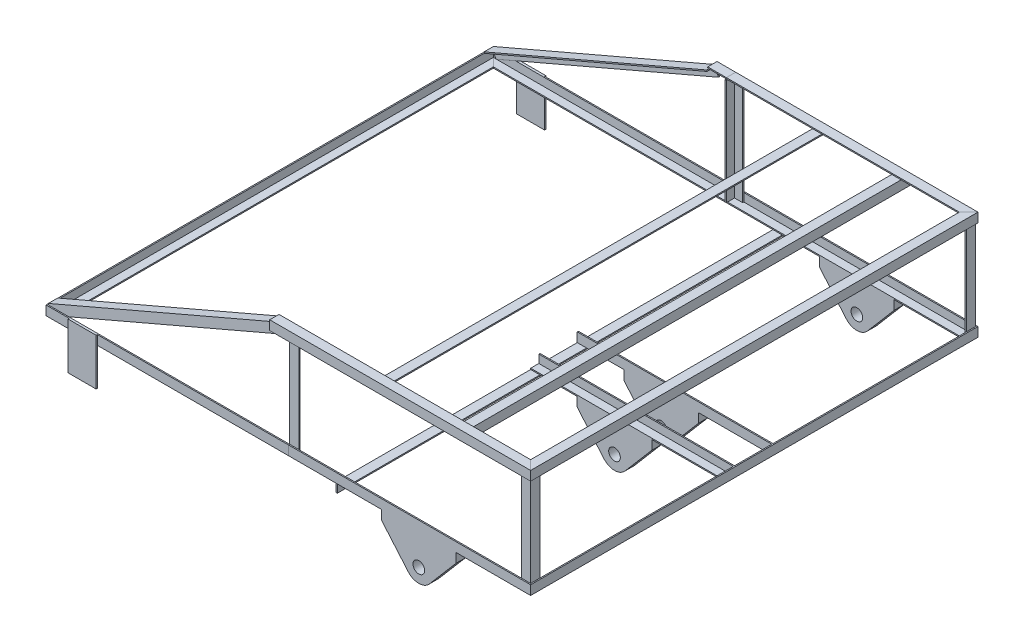
SolidWorks part; units mm, degrees
ref_plane "Front Plane" through (0, 0, 0) normal (0, 0, 1) x (1, 0, 0)
ref_plane "Top Plane" through (0, 0, 0) normal (0, 1, 0) x (1, 0, 0)
ref_plane "Right Plane" through (0, 0, 0) normal (1, 0, 0) x (0, 0, -1)
sketch "Sketch1" plane through (0, 0, 0) normal (0, 1, 0) x (1, 0, 0)
  line L1 (-330.2, -304.8) -> (330.2, -304.8)
  line L2 (-330.2, -304.8) -> (-330.2, 304.8)
  line L3 (-330.2, 304.8) -> (330.2, 304.8)
  line L4 (330.2, -304.8) -> (330.2, 304.8)
  line L5 (-330.2, -304.8) -> (330.2, 304.8) construction
  line L6 (-330.2, 304.8) -> (330.2, -304.8) construction
  point P0 (0, 0)
  dimension "D1" = 660.4
  dimension "D2" = 609.6
sketch "Sketch2" plane through (0, 0, 0) normal (1, 0, 0) x (0, 0, -1)
  line L0 (-304.8, 0) -> (-292.1, 0)
  line L1 (304.8, 0) -> (-304.8, 0) construction
  line L2 (-304.8, 0) -> (304.8, 0) construction
  line L3 (-292.1, 0) -> (-292.1, 1.5875)
  line L4 (-292.1, 1.5875) -> (-303.2125, 1.5875)
  line L5 (-303.2125, 1.5875) -> (-303.2125, 12.7)
  line L6 (-303.2125, 12.7) -> (-304.8, 12.7)
  line L7 (-304.8, 12.7) -> (-304.8, 0)
  dimension "D1" = 1.5875
  dimension "D2" = 12.7
sweep "Sweep1" add profiles "Sketch2" path "Sketch1"
sketch "Sketch3" plane through (0, 0, 0) normal (0, 0, 1) x (1, 0, 0)
  line L0 (-330.2, 12.7) -> (-330.2, 0) construction
  line L1 (-330.2, -144.4625) -> (330.2, -144.4625)
  line L2 (-330.2, -144.4625) -> (-330.2, 147.6375)
  line L3 (-330.2, 147.6375) -> (330.2, 147.6375)
  line L4 (330.2, -144.4625) -> (330.2, 147.6375)
  line L5 (-330.2, -144.4625) -> (330.2, 147.6375) construction
  line L6 (-330.2, 147.6375) -> (330.2, -144.4625) construction
  line L7 (0, 0) -> (330.2, 0) construction
  point P0 (0, 1.5875)
  dimension "D1" = 292.1
  dimension "D2" = 144.4625
ref_plane "Plane1" through (0, 147.6375, 0) normal (0, 1, 0) x (1, 0, 0)
sketch "Sketch4" plane through (0, 147.6375, 0) normal (0, 1, 0) x (1, 0, 0)
  line L1 (-330.2, -304.8) -> (330.2, -304.8)
  line L2 (-330.2, -304.8) -> (-330.2, 304.8)
  line L3 (-330.2, 304.8) -> (330.2, 304.8)
  line L4 (330.2, -304.8) -> (330.2, 304.8)
  line L5 (-330.2, -304.8) -> (330.2, 304.8) construction
  line L6 (-330.2, 304.8) -> (330.2, -304.8) construction
sketch "Sketch5" plane through (0, 0, 0) normal (1, 0, 0) x (0, 0, -1)
  line L0 (304.8, 147.6375) -> (304.8, 134.9375)
  line L1 (304.8, 147.6375) -> (-304.8, 147.6375) construction
  line L2 (-304.8, 147.6375) -> (304.8, 147.6375) construction
  line L3 (304.8, 134.9375) -> (303.2125, 134.9375)
  line L4 (303.2125, 134.9375) -> (303.2125, 146.05)
  line L5 (303.2125, 146.05) -> (292.1, 146.05)
  line L6 (292.1, 146.05) -> (292.1, 147.6375)
  line L7 (292.1, 147.6375) -> (304.8, 147.6375)
  dimension "D1" = 1.5875
  dimension "D2" = 12.7
sweep "Sweep2" add profiles "Sketch5" path "Sketch4"
sketch "Sketch6" plane through (0, 1.5875, 0) normal (0, 1, 0) x (1, 0, 0)
  line L12 (0, -303.2125) -> (328.6125, -303.2125) construction
  line L17 (315.9125, -303.2125) -> (328.6125, -303.2125)
  line L18 (328.6125, -303.2125) -> (328.6125, -290.5125)
  line L19 (328.6125, -303.2125) -> (328.6125, 303.2125) construction
  line L20 (328.6125, -290.5125) -> (327.025, -290.5125)
  line L21 (327.025, -290.5125) -> (327.025, -301.625)
  line L22 (328.6125, -303.2125) -> (317.5, -292.1) construction
  line L23 (327.025, -301.625) -> (315.9125, -301.625)
  line L24 (315.9125, -301.625) -> (315.9125, -303.2125)
  line L27 (0, -303.2125) -> (12.7, -303.2125) construction
  line L28 (12.7, -303.2125) -> (12.7, -301.625)
  line L29 (12.7, -301.625) -> (1.5875, -301.625)
  line L30 (1.5875, -301.625) -> (1.5875, -290.5125)
  line L31 (1.5875, -290.5125) -> (0, -290.5125)
  line L32 (0, -290.5125) -> (0, -303.2125)
  line L33 (0, -303.2125) -> (12.7, -303.2125)
  dimension "D3" = 12.7
  dimension "D4" = 1.5875
  dimension "D5" = 12.7
  dimension "D6" = 1.5875
extrude "Boss-Extrude4" add sketch "Sketch6" along normal up to surface (144.4625 mm away) up to face at (0, 146.05, 297.6562)
mirror "Mirror1" about plane through (0, 0, 0) normal (0, 0, 1) of "Boss-Extrude4"
sketch "Sketch7" plane through (0, 0, 303.2125) normal (0, 0, -1) x (-1, 0, 0)
  line L29 (-238.125, 146.05) -> (-238.125, 133.35)
  line L30 (-315.9125, 146.05) -> (-12.7, 146.05) construction
  line L31 (-238.125, 133.35) -> (-236.5375, 133.35)
  line L32 (-236.5375, 133.35) -> (-236.5375, 144.4625)
  line L33 (-236.5375, 144.4625) -> (-225.425, 144.4625)
  line L48 (-225.425, 144.4625) -> (-225.425, 146.05)
  line L49 (-225.425, 146.05) -> (-238.125, 146.05)
  line L50 (-130.175, 146.05) -> (-117.475, 146.05)
  line L51 (-117.475, 146.05) -> (-117.475, 133.35)
  line L52 (-117.475, 133.35) -> (-119.0625, 133.35)
  line L53 (-119.0625, 133.35) -> (-119.0625, 144.4625)
  line L54 (-119.0625, 144.4625) -> (-130.175, 144.4625)
  line L55 (-130.175, 144.4625) -> (-130.175, 146.05)
  line L57 (-225.425, 146.05) -> (-130.175, 146.05) construction
  line L59 (-330.2, 0) -> (330.2, 0) construction
  line L65 (-76.2, 0) -> (-76.2, -1.5875)
  line L66 (-76.2, -1.5875) -> (-65.0875, -1.5875)
  line L67 (-65.0875, -1.5875) -> (-65.0875, -12.7)
  line L68 (-65.0875, -12.7) -> (-63.5, -12.7)
  line L69 (-63.5, -12.7) -> (-63.5, 0)
  line L70 (-63.5, 0) -> (-76.2, 0)
  line L71 (-76.2, 0) -> (-279.4, 0) construction
  line L72 (-330.2, 134.9375) -> (-330.2, 147.6375) construction
  point P13 (-177.8, 146.05)
  point P20 (-177.8, 0)
  dimension "D1" = 12.7
  dimension "D2" = 1.5875
  dimension "D3" = 117.475
  dimension "D4" = 203.2
  dimension "D5" = 152.4
extrude "Boss-Extrude5" add sketch "Sketch7" along normal up to surface (606.425 mm away) up to face at (-164.3062, 140.4937, -303.2125)
sketch "Sketch8" plane through (0, 0, 0) normal (0, 0, 1) x (1, 0, 0)
  line L0 (236.5375, 144.4625) -> (119.0625, 144.4625) construction
  line L1 (177.8, 144.4625) -> (177.8, -42.8625) construction
  line L2 (-330.2, 0) -> (0, 0) construction
  line L3 (127, -12.7) -> (127, 0)
  line L4 (127, 0) -> (228.6, 0)
  line L5 (228.6, 0) -> (228.6, -12.7)
  line L6 (228.6, -12.7) -> (192.288, -55.2318)
  line L7 (127, -12.7) -> (163.312, -55.2318)
  line L8 (330.2, 0) -> (-330.2, 0) construction
  circle A0 centre (177.8, -42.8625) radius 7.9375
  arc A2 (163.312, -55.2318) -> (192.288, -55.2318) centre (177.8, -42.8625) ccw
  point P17 (177.8, 0)
  dimension "D2" = 15.875
  dimension "D3" = 101.6
  dimension "D4" = 38.1
  dimension "D1" = 42.8625
  dimension "D5" = 12.7
extrude "Boss-Extrude6" add sketch "Sketch8" against normal blind 12.7 from surface at 304.8 starting at face at (-165.1, 6.35, 304.8)
sketch "Sketch11" plane through (0, 0, -304.8) normal (0, 0, -1) x (-1, 0, 0)
  line L3 (-127, -12.7) -> (-127, 0)
  line L4 (-127, 0) -> (-228.6, 0)
  line L5 (-228.6, 0) -> (-228.6, -12.7)
  line L6 (-127, -12.7) -> (-127, 0)
  line L7 (-127, 0) -> (-228.6, 0)
  line L8 (-228.6, 0) -> (-228.6, -12.7)
  line L11 (-228.6, -12.7) -> (-192.288, -55.2318)
  line L12 (-228.6, -12.7) -> (-192.288, -55.2318)
  line L13 (-163.312, -55.2318) -> (-127, -12.7)
  line L14 (-163.312, -55.2318) -> (-127, -12.7)
  circle A1 centre (-177.8, -42.8625) radius 7.9375
  circle A2 centre (-177.8, -42.8625) radius 7.9375
  arc A3 (-192.288, -55.2318) -> (-163.312, -55.2318) centre (-177.8, -42.8625) ccw
  arc A5 (-192.288, -55.2318) -> (-163.312, -55.2318) centre (-177.8, -42.8625) ccw
  dimension "D1" = 0
  dimension "D2" = 0
extrude "Boss-Extrude11" add sketch "Sketch11" against normal up to surface (12.7 mm away) up to face at (17.6609, 0.7938, -292.1)
sketch "Sketch12" plane through (63.5, 0, 0) normal (-1, 0, 0) x (0, 0, 1)
  line L0 (-25.4, 0) -> (-25.4, 12.7)
  line L1 (-292.1, 0) -> (292.1, 0) construction
  line L2 (-25.4, 12.7) -> (-26.9875, 12.7)
  line L3 (-26.9875, 12.7) -> (-26.9875, 1.5875)
  line L4 (-26.9875, 1.5875) -> (-38.1, 1.5875)
  line L5 (-38.1, 1.5875) -> (-38.1, 0)
  line L6 (-38.1, 0) -> (-25.4, 0)
  line L7 (25.4, 0) -> (25.4, 12.7)
  line L8 (25.4, 12.7) -> (26.9875, 12.7)
  line L9 (26.9875, 12.7) -> (26.9875, 1.5875)
  line L10 (26.9875, 1.5875) -> (38.1, 1.5875)
  line L11 (38.1, 1.5875) -> (38.1, 0)
  line L12 (38.1, 0) -> (25.4, 0)
  line L13 (-25.4, 0) -> (25.4, 0) construction
  point P10 (0, 0)
  dimension "D1" = 1.5875
  dimension "D2" = 12.7
  dimension "D3" = 50.8
extrude "Boss-Extrude12" add sketch "Sketch12" against normal up to surface (265.1125 mm away) up to face at (328.6125, 7.1438, 0)
sketch "Sketch13" plane through (0, 0, -38.1) normal (0, 0, -1) x (-1, 0, 0)
  line L21 (-1.5875, 1.5875) -> (-317.5, 1.5875)
  line L22 (0, 1.5875) -> (-1.5875, 1.5875)
  line L23 (317.5, 1.5875) -> (0, 1.5875)
  line L24 (317.5, 0) -> (317.5, 1.5875)
  line L25 (-63.5, 0) -> (317.5, 0)
  line L26 (-76.2, 0) -> (-63.5, 0)
  line L27 (-127, 0) -> (-76.2, 0)
  line L28 (-127, -12.7) -> (-127, 0)
  line L29 (-163.312, -55.2318) -> (-127, -12.7)
  line L30 (-228.6, -12.7) -> (-192.288, -55.2318)
  line L31 (-228.6, 0) -> (-228.6, -12.7)
  line L32 (-317.5, 0) -> (-228.6, 0)
  line L35 (-317.5, 1.5875) -> (-317.5, 0)
  line L39 (317.5, 0) -> (317.5, 1.5875)
  line L40 (-63.5, 0) -> (317.5, 0)
  line L41 (-76.2, 0) -> (-63.5, 0)
  line L50 (-317.5, 1.5875) -> (-317.5, 0)
  line L51 (-127, -12.7) -> (-127, 0) construction
  line L52 (-163.312, -55.2318) -> (-127, -12.7) construction
  line L53 (-228.6, -12.7) -> (-192.288, -55.2318) construction
  line L54 (-228.6, 0) -> (-228.6, -12.7) construction
  line L55 (-127, -12.7) -> (-127, 0)
  line L56 (-163.312, -55.2318) -> (-127, -12.7)
  line L57 (-228.6, -12.7) -> (-192.288, -55.2318)
  line L58 (-228.6, 0) -> (-228.6, -12.7)
  line L59 (-127, 0) -> (-228.6, 0)
  arc A5 (-192.288, -55.2318) -> (-163.312, -55.2318) centre (-177.8, -42.8625) ccw
  circle A7 centre (-177.8, -42.8625) radius 7.9375 construction
  arc A8 (-192.288, -55.2318) -> (-163.312, -55.2318) centre (-177.8, -42.8625) ccw construction
  circle A9 centre (-177.8, -42.8625) radius 7.9375
  arc A10 (-192.288, -55.2318) -> (-163.312, -55.2318) centre (-177.8, -42.8625) ccw
  line M3 (-317.5, 0) -> (-76.2, 0)
  dimension "D1" = 0
sketch "Sketch14" plane through (0, 0, 38.1) normal (0, 0, 1) x (1, 0, 0)
  line L0 (228.6, 0) -> (228.6, -12.7) construction
  line L1 (127, -12.7) -> (127, 0) construction
  line L2 (127, 0) -> (228.6, 0) construction
  line L3 (228.6, 0) -> (228.6, -12.7)
  line L4 (127, -12.7) -> (127, 0)
  line L5 (127, 0) -> (228.6, 0)
  line L6 (317.5, 0) -> (317.5, 1.5875)
  line L7 (317.5, 1.5875) -> (63.5, 1.5875)
  line L8 (63.5, 1.5875) -> (63.5, 0)
  line L9 (63.5, 0) -> (76.2, 0)
  line L10 (76.2, 0) -> (317.5, 0)
  line L11 (317.5, 0) -> (317.5, 1.5875)
  line L13 (317.5, 1.5875) -> (63.5, 1.5875)
  line L14 (63.5, 1.5875) -> (63.5, 0)
  line L15 (63.5, 0) -> (76.2, 0)
  line L16 (76.2, 0) -> (317.5, 0)
  line L18 (163.312, -55.2318) -> (127, -12.7) construction
  line L19 (228.6, -12.7) -> (192.288, -55.2318) construction
  line L20 (163.312, -55.2318) -> (127, -12.7)
  line L21 (228.6, -12.7) -> (192.288, -55.2318)
  circle A1 centre (177.8, -42.8625) radius 7.9375 construction
  circle A3 centre (177.8, -42.8625) radius 7.9375
  circle A4 centre (177.8, -42.8625) radius 7.9375 construction
  arc A5 (163.312, -55.2318) -> (192.288, -55.2318) centre (177.8, -42.8625) ccw construction
  circle A6 centre (177.8, -42.8625) radius 7.9375
  arc A7 (163.312, -55.2318) -> (192.288, -55.2318) centre (177.8, -42.8625) ccw
  line M11 (76.2, 0) -> (317.5, 0)
  dimension "D1" = 0
extrude "Boss-Extrude15" add sketch "Sketch13" against normal up to surface (12.7 mm away) contours L57 A10 L56 L55 L58 A9 M3 up to face at (213.6321, 4.0821, -25.4)
extrude "Boss-Extrude16" add sketch "Sketch14" against normal up to surface (12.7 mm away) contours L20 A7 L21 L3 L4 A3 M11 up to face at (213.6321, 4.0821, 25.4)
sketch "Sketch15" plane through (0, 12.7, 0) normal (0, 1, 0) x (1, 0, 0)
  line L0 (330.2, 304.8) -> (-330.2, 304.8) construction
  line L1 (-260.35, 304.8) -> (-298.45, 304.8)
  line L2 (-260.35, 304.8) -> (-260.35, 306.3875)
  line L3 (-260.35, 306.3875) -> (-298.45, 306.3875)
  line L4 (-298.45, 304.8) -> (-298.45, 306.3875)
  line L5 (-330.2, -304.8) -> (0, -304.8) construction
  line L6 (-260.35, -304.8) -> (-298.45, -304.8)
  line L7 (-260.35, -304.8) -> (-260.35, -306.3875)
  line L8 (-260.35, -306.3875) -> (-298.45, -306.3875)
  line L9 (-298.45, -304.8) -> (-298.45, -306.3875)
  line L10 (-330.2, 304.8) -> (-279.4, 304.8) construction
  line L11 (-330.2, -304.8) -> (-330.2, 304.8) construction
  point P17 (-279.4, -304.8)
  dimension "D1" = 50.8
  dimension "D2" = 50.8
  dimension "D3" = 38.1
  dimension "D4" = 1.5875
extrude "Boss-Extrude17" add sketch "Sketch15" against normal offset from surface (63.5 mm away) 50.8 up to face at (-161.925, 0, 298.45) offset beyond the face yes
sketch "Sketch16" plane through (0, 0, 306.3875) normal (0, 0, 1) x (1, 0, 0)
  line L0 (-298.45, -50.8) -> (-260.35, -50.8) construction
  point P0 (-279.4, -42.8625)
  point P1 (177.8, -42.8625)
  point P4 (-279.4, -50.8)
sketch "Sketch17" plane through (0, 0, -306.3875) normal (0, 0, -1) x (-1, 0, 0)
  line L0 (260.35, -50.8) -> (298.45, -50.8) construction
  point P0 (279.4, -42.8625)
  point P4 (279.4, -50.8)
  point P5 (-177.8, -42.8625)
sketch "Sketch18" plane through (0, 0, -304.8) normal (0, 0, -1) x (-1, 0, 0)
  line L0 (0, 134.9375) -> (0, 12.7) construction
  line L1 (25.4, 134.9375) -> (330.2, 134.9375)
  line L2 (25.4, 134.9375) -> (25.4, 147.6375)
  line L3 (25.4, 147.6375) -> (330.2, 147.6375)
  line L4 (330.2, 134.9375) -> (330.2, 147.6375)
  dimension "D1" = 25.4
extrude "Cut-Extrude1" cut sketch "Sketch18" against normal up to surface (609.6 mm away) up to face at (0, 141.2875, 304.8)
sketch "Sketch19" plane through (0, 0, -303.2125) normal (0, 0, 1) x (1, 0, 0)
  line L0 (-25.4, 144.78) -> (-328.6125, 14.5264)
  line L1 (-328.6125, 14.5264) -> (-323.5998, 2.8575)
  line L2 (-323.5998, 2.8575) -> (-20.3873, 133.1111)
  line L3 (-20.3873, 133.1111) -> (-25.4, 144.78)
  line L4 (-328.6125, 12.7) -> (-328.6125, 1.5875) construction
  line L6 (0, 1.5875) -> (-328.6125, 1.5875) construction
  line L7 (-25.4, 134.9375) -> (-25.4, 146.05) construction
  line L8 (-25.4, 146.05) -> (0, 146.05) construction
  point P4 (0, 0)
  point P9 (0, 0)
  point P10 (-323.5582, 2.8606)
  point P12 (-328.6125, 11.4224)
  point P13 (-328.6125, 13.2202)
  point P15 (-25.4, 145.5347)
  dimension "D1" = 12.7
  dimension "D2" = 1.27
  dimension "D3" = 1.27
extrude "Boss-Extrude21" add sketch "Sketch19" along normal blind 1.5875
sketch "Sketch20" plane through (0, 0, -303.2125) normal (0, 0, -1) x (-1, 0, 0)
  line L0 (25.4, 144.78) -> (328.6125, 14.5264)
  line L1 (328.6125, 14.5264) -> (327.9859, 13.0678)
  line L2 (328.6125, 14.5264) -> (327.8279, 12.7) construction
  line L3 (327.9859, 13.0678) -> (24.7734, 143.3214)
  line L4 (21.1719, 134.9375) -> (25.4, 144.78) construction
  line L5 (24.7734, 143.3214) -> (25.4, 144.78)
  dimension "D1" = 1.5875
extrude "Boss-Extrude23" add sketch "Sketch20" against normal blind 12.7
mirror "Mirror2" about plane through (0, 0, 0) normal (0, 0, 1) of "Boss-Extrude23", "Boss-Extrude21"
